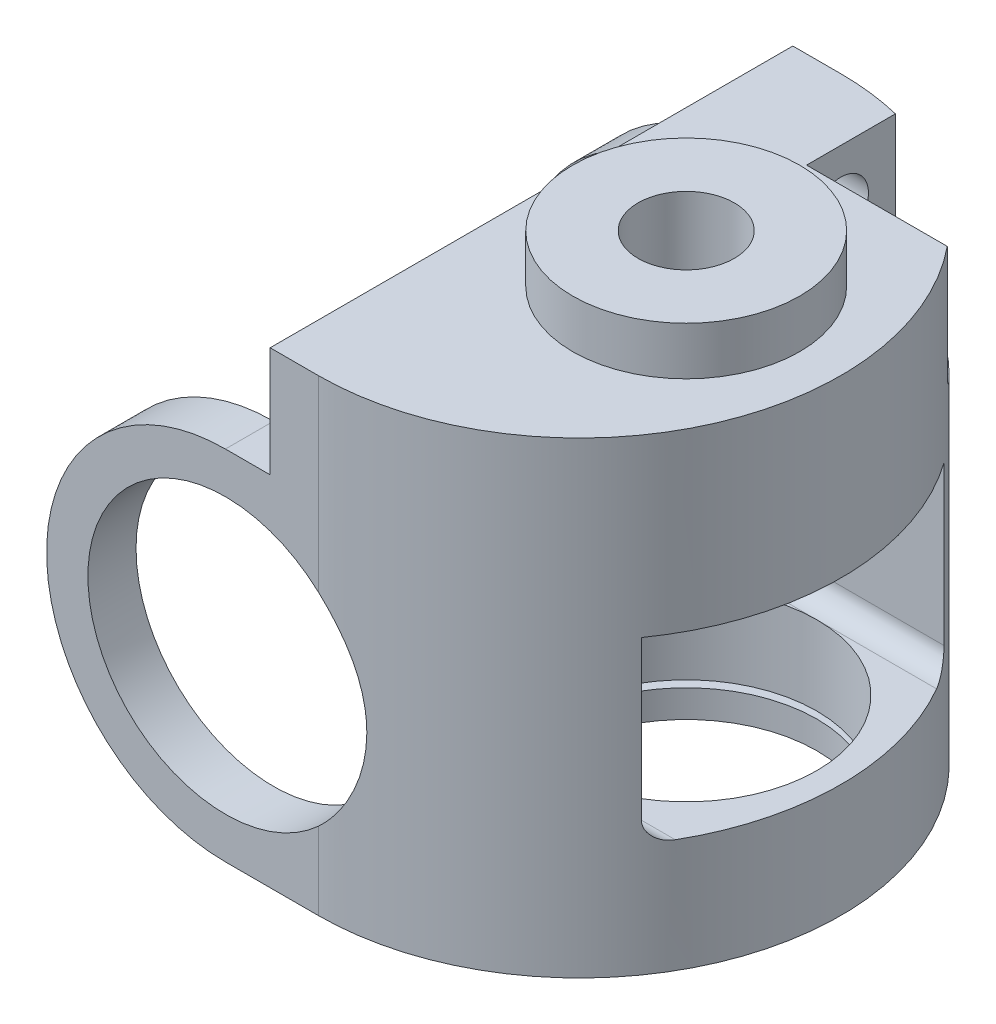
SolidWorks part; units mm, degrees
ref_plane "Plan de face" through (0, 0, 0) normal (0, 0, 1) x (1, 0, 0)
ref_plane "Plan de dessus" through (0, 0, 0) normal (0, 1, 0) x (1, 0, 0)
ref_plane "Plan de droite" through (0, 0, 0) normal (1, 0, 0) x (0, 0, -1)
sketch "Sketch2" plane through (0, 0, 0) normal (0, 1, 0) x (1, 0, 0)
  line L0 (-3.5, -19) -> (-3.5, 19)
  line L1 (-3.5, 19) -> (0, 19)
  line L2 (-3.5, -19) -> (0, -19)
  line L3 (19, 0) -> (19, 16.5672) construction
  arc A0 (0, -19) -> (0, 19) centre (0, 0) ccw
  circle A1 centre (7.75, 0) radius 3.5
  point P7 (-3.5, 0)
  dimension "D1" = 19
  dimension "D3" = 22.5
  dimension "D4" = 11.25
  dimension "D5" = 7
  dimension "D2" = 38
extrude "Boss-Extrude1" add sketch "Sketch2" along normal blind 34
sketch "Sketch19" plane through (0, 34, 0) normal (0, 1, 0) x (1, 0, 0)
  circle A0 centre (7.75, 0) radius 8.25
  circle A1 centre (7.75, 0) radius 3.5
  dimension "D1" = 16.5
  dimension "D2" = 7
extrude "Boss-Extrude3" add sketch "Sketch19" along normal blind 3.5
sketch "Sketch3" plane through (0, 0, 19) normal (0, 0, 1) x (1, 0, 0)
  line L3 (-3.5, 0) -> (-6.75, 0)
  line L4 (-6.75, 26) -> (-3.5, 26)
  line L5 (-3.5, 34) -> (-3.5, 0) construction
  arc A0 (-6.75, 26) -> (-6.75, 0) centre (-6.75, 13) ccw
  line M4 (-3.5, 34) -> (-3.5, 0)
  dimension "D1" = 26
  dimension "D2" = 3.25
extrude "Boss-Extrude2" add sketch "Sketch3" against normal blind 3.5 contours A0 M4
sketch "Sketch4" plane through (0, 0, 19) normal (0, 0, 1) x (1, 0, 0)
  circle A0 centre (-6.75, 13) radius 10
  dimension "D1" = 20
extrude "Cut-Extrude1" cut sketch "Sketch4" against normal up to surface (3.5 mm away) up to face at (-8.375, 13, 15.5)
pattern_linear "LPattern4" count 2 spacing 34.5 along (0, 0, -1) of "Boss-Extrude2", "Cut-Extrude1"
sketch "Sketch6" plane through (-3.5, 0, 0) normal (1, 0, 0) x (0, 0, -1)
  line L0 (15.5, 0) -> (-15.5, 0) construction
  line L1 (11, 21.25) -> (-11, 21.25)
  line L2 (11, 21.25) -> (11, 9.75)
  line L3 (9.5, 8.25) -> (-9.5, 8.25)
  line L4 (-11, 21.25) -> (-11, 9.75)
  arc A0 (-11, 9.75) -> (-9.5, 8.25) centre (-9.5, 9.75) ccw
  arc A1 (11, 9.75) -> (9.5, 8.25) centre (9.5, 9.75) cw
  point P6 (0, 8.25)
  point P10 (-11, 8.25)
  point P13 (11, 8.25)
  dimension "D4" = 1.5
  dimension "D1" = 8.25
  dimension "D2" = 22
  dimension "D3" = 13
extrude "Cut-Extrude3" cut sketch "Sketch6" along normal through all
sketch "Sketch7" plane through (0, 0, 15.5) normal (0, 0, -1) x (-1, 0, 0)
  circle A3 centre (6.75, 13) radius 13.5
  dimension "D3" = 27
extrude "Cut-Extrude4" cut sketch "Sketch7" along normal blind 4.5 contours A3
pattern_linear "LPattern3" count 2 spacing 26.5 along (0, 0, -1) of "Cut-Extrude4"
sketch "Sketch16" plane through (-3.5, 0, 0) normal (-1, 0, 0) x (0, 0, 1)
  line L0 (19, 34) -> (19, 26) construction
  line L1 (-19, 34) -> (19, 34) construction
  point P0 (11, 31.5)
  dimension "D1" = 8
  dimension "D2" = 2.5
hole_wizard "M2 Tapped Hole1" positions "Sketch16" profile "Sketch15" tap size "M2" standard "ISO"
sketch "Sketch15" plane through (-3.5, 31.5, 11) normal (0, 1, 0) x (0, 0, 1)
  line L0 (0, 0) -> (0, 5.9807)
  line L1 (0, 5.9807) -> (0.8, 5.5)
  line L2 (0.8, 5.5) -> (0.8, 0)
  line L5 (0.8, 0) -> (0, 0)
  line L10 (0, 5.9807) -> (-0.8, 5.5) construction
  line L11 (0, -6.35) -> (0, 107.95) construction
  dimension "Tap Drill Dia." = 1.6
  dimension "Tap Drill Depth" = 5.5
  dimension "Drill Angle" = 118
cosmetic thread "Hole Thread1" parameters "D1"=4.5, "D2"=2
sketch "Sketch17" plane through (-3.5, 0, 0) normal (-1, 0, 0) x (0, 0, 1)
  line L0 (-19, 34) -> (-19, 26) construction
  line L1 (-19, 34) -> (19, 34) construction
  circle A1 centre (-14.5, 30) radius 2
  dimension "D1" = 4
  dimension "D2" = 4.5
  dimension "D3" = 4
extrude "Cut-Extrude5" cut sketch "Sketch17" against normal blind 8
sketch "Sketch18" plane through (4.5, 0, 0) normal (-1, 0, 0) x (0, 0, 1)
  line L0 (-19, 34) -> (-19, 26) construction
  line L1 (-19, 24.5) -> (-13.5, 24.5)
  line L2 (-19, 24.5) -> (-19, 34)
  line L3 (-19, 34) -> (-12, 34)
  line L4 (-12, 26) -> (-12, 34)
  line L5 (-19, 34) -> (19, 34) construction
  arc A2 (-12, 26) -> (-13.5, 24.5) centre (-13.5, 26) cw
  dimension "D1" = 9.5
  dimension "D2" = 7
  dimension "D3" = 1.5
extrude "Cut-Extrude6" cut sketch "Sketch18" against normal up to next
sketch "Sketch20" plane through (0, 21.25, 0) normal (0, -1, 0) x (1, 0, 0)
  circle A0 centre (7.75, 0) radius 9.75
  dimension "D1" = 19.5
extrude "Cut-Extrude7" cut sketch "Sketch20" against normal blind 6.25
sketch "Sketch21" plane through (0, 27.5, 0) normal (0, -1, 0) x (1, 0, 0)
  circle A0 centre (7.75, 0) radius 8.5
  dimension "D1" = 17
extrude "Cut-Extrude8" cut sketch "Sketch21" against normal blind 0.5
sketch "Sketch22" plane through (0, 8.25, 0) normal (0, 1, 0) x (1, 0, 0)
  circle A0 centre (7.75, 0) radius 9.5
  dimension "D1" = 19
extrude "Cut-Extrude9" cut sketch "Sketch22" against normal blind 5.75
sketch "Sketch23" plane through (0, 2.5, 0) normal (0, 1, 0) x (1, 0, 0)
  circle A0 centre (7.75, 0) radius 10.5
  dimension "D1" = 21
extrude "Cut-Extrude10" cut sketch "Sketch23" against normal blind 0.5
sketch "Sketch24" plane through (0, 2, 0) normal (0, 1, 0) x (1, 0, 0)
  circle A0 centre (7.75, 0) radius 9.5
  dimension "D1" = 19
extrude "Cut-Extrude11" cut sketch "Sketch24" against normal blind 2
